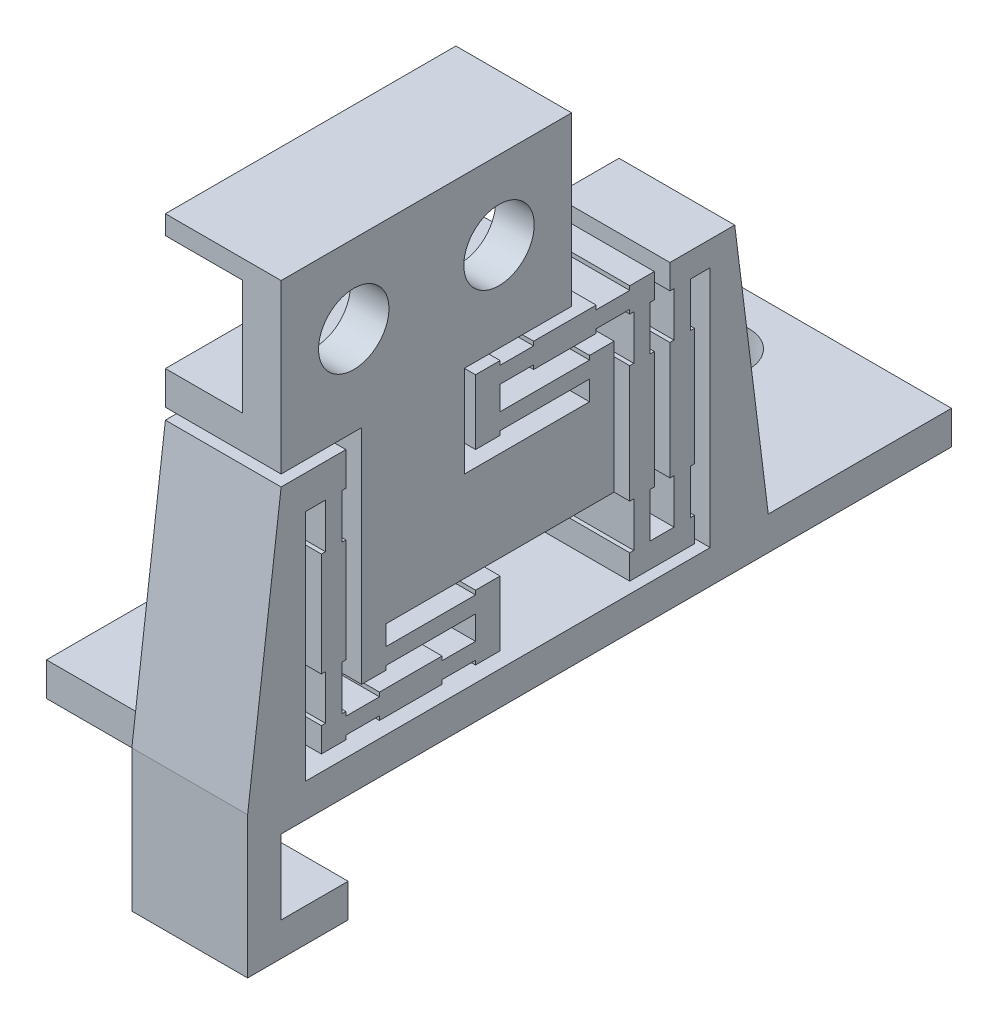
SolidWorks part; units mm, degrees
ref_plane "Front Plane" through (0, 0, 0) normal (0, 0, 1) x (1, 0, 0)
ref_plane "Top Plane" through (0, 0, 0) normal (0, 1, 0) x (1, 0, 0)
ref_plane "Right Plane" through (0, 0, 0) normal (1, 0, 0) x (0, 0, -1)
sketch "Sketch1" plane through (0, 0, 0) normal (1, 0, 0) x (0, 0, -1)
  line L0 (0, 0) -> (13, 0)
  line L1 (13, 0) -> (13, -7.5)
  line L2 (0, 0) -> (0, -7.5)
  line L3 (0, -7.5) -> (3.6, -7.5)
  line L4 (3.6, -7.5) -> (3.6, -17.45)
  line L5 (4.7, -17.2667) -> (8.7, -17.2667)
  line L6 (8.7, -17.2667) -> (8.7, -18.3333)
  line L7 (2.9, -18.15) -> (2.7167, -18.15)
  line L8 (2.9, -16.15) -> (2.9, -11.5)
  line L9 (2.9, -8) -> (0, -8)
  line L10 (0, -8) -> (-1.5, -19.95)
  line L11 (13, -7.5) -> (8.2, -7.5)
  line L12 (8.2, -7.5) -> (8.2, -11.6)
  line L13 (8.2, -11.6) -> (13.8, -11.6)
  line L14 (13.8, -11.6) -> (13.8, -10.7167)
  line L15 (9.8, -10.9) -> (8.7, -10.9)
  line L16 (8.7, -10.9) -> (8.7, -8)
  line L17 (8.7, -8) -> (9.8, -8)
  line L18 (14.9, -9.8) -> (14.9, -15.65)
  line L19 (14.9, -15.65) -> (4.7, -15.65)
  line L20 (4.7, -15.65) -> (4.7, -16.5333)
  line L21 (8.7, -16.35) -> (9.8, -16.35)
  line L22 (9.8, -16.35) -> (9.8, -19.25)
  line L23 (9.8, -19.25) -> (8.7, -19.25)
  line L24 (1.8, -19.25) -> (1.8, -18.15)
  line L25 (1.9833, -9.5) -> (1.1, -9.5)
  line L26 (1.1, -9.5) -> (1.1, -19.95)
  line L27 (1.1, -19.95) -> (19.2, -19.95)
  line L28 (14.9, -9.8) -> (13.8, -9.8)
  line L29 (9.8, -9.9833) -> (9.8, -8.9167)
  line L30 (11.3, -9.1) -> (14.1, -9.1)
  line L31 (15.6, -11.1) -> (15.6, -16.35)
  line L32 (16.7, -8) -> (16.7, -9.1)
  line L33 (16.5167, -18.35) -> (17.5833, -18.35)
  line L34 (17.4, -16.35) -> (17.4, -11.1)
  line L35 (17.4, -8) -> (20.3, -8)
  line L36 (15.6, -19.45) -> (18.5, -19.45)
  line L37 (18.5, -19.45) -> (18.5, -18.35)
  line L38 (18.3167, -9.1) -> (19.2, -9.1)
  line L39 (19.2, -9.1) -> (19.2, -19.95)
  line L45 (0, -21.45) -> (21.8, -21.45)
  line L47 (21.8, -21.45) -> (21.8, -19.95)
  line L49 (20.3, -8) -> (21.8, -19.95)
  line L51 (-1.5, -19.95) -> (-1.5, -26.28)
  line L52 (-1.5, -26.28) -> (3, -26.28)
  line L53 (3, -26.28) -> (3, -24.78)
  line L54 (3, -24.78) -> (0, -24.78)
  line L55 (0, -24.78) -> (0, -21.45)
  line L57 (1.9833, -9.5) -> (1.9833, -11.5)
  line L58 (1.9833, -11.5) -> (1.8, -11.5)
  line L59 (2.9, -9.5) -> (2.7167, -9.5)
  line L60 (2.7167, -9.5) -> (2.7167, -11.5)
  line L61 (2.7167, -11.5) -> (2.9, -11.5)
  line L63 (2.7167, -18.15) -> (2.7167, -16.15)
  line L64 (2.7167, -16.15) -> (2.9, -16.15)
  line L65 (1.8, -18.15) -> (1.9833, -18.15)
  line L66 (1.9833, -18.15) -> (1.9833, -16.15)
  line L67 (1.9833, -16.15) -> (1.8, -16.15)
  line L75 (15.6, -9.1) -> (15.7833, -9.1)
  line L76 (15.7833, -9.1) -> (15.7833, -11.1)
  line L77 (15.7833, -11.1) -> (15.6, -11.1)
  line L78 (16.7, -9.1) -> (16.5167, -9.1)
  line L79 (16.5167, -9.1) -> (16.5167, -11.1)
  line L80 (2.9, -9.5) -> (2.9, -8)
  line L81 (1.8, -16.15) -> (1.8, -11.5)
  line L82 (16.5167, -11.1) -> (16.7, -11.1)
  line L83 (16.7, -11.1) -> (16.7, -16.35)
  line L84 (16.7, -16.35) -> (16.5167, -16.35)
  line L85 (16.5167, -16.35) -> (16.5167, -18.35)
  line L86 (15.6, -16.35) -> (15.7833, -16.35)
  line L87 (15.7833, -16.35) -> (15.7833, -18.35)
  line L88 (15.7833, -18.35) -> (15.6, -18.35)
  line L89 (15.6, -18.35) -> (15.6, -19.45)
  line L90 (17.4, -16.35) -> (17.5833, -16.35)
  line L91 (17.5833, -16.35) -> (17.5833, -18.35)
  line L92 (18.5, -16.35) -> (18.3167, -16.35)
  line L93 (18.3167, -16.35) -> (18.3167, -18.35)
  line L94 (18.3167, -18.35) -> (18.5, -18.35)
  line L95 (18.5, -11.1) -> (18.3167, -11.1)
  line L96 (18.3167, -11.1) -> (18.3167, -9.1)
  line L97 (17.4, -11.1) -> (17.5833, -11.1)
  line L98 (17.5833, -11.1) -> (17.5833, -9.1)
  line L99 (17.5833, -9.1) -> (17.4, -9.1)
  line L100 (17.4, -9.1) -> (17.4, -8)
  line L101 (18.5, -16.35) -> (18.5, -11.1)
  line L102 (9.8, -8) -> (9.8, -8.1833)
  line L103 (9.8, -8.1833) -> (11.3, -8.1833)
  line L104 (11.3, -8.1833) -> (11.3, -8)
  line L105 (11.3, -9.1) -> (11.3, -8.9167)
  line L106 (11.3, -8.9167) -> (9.8, -8.9167)
  line L108 (15.6, -8) -> (15.6, -8.1833)
  line L109 (15.6, -8.1833) -> (14.1, -8.1833)
  line L110 (14.1, -8.1833) -> (14.1, -8)
  line L111 (14.1, -9.1) -> (14.1, -8.9167)
  line L112 (14.1, -8.9167) -> (15.6, -8.9167)
  line L113 (15.6, -8.9167) -> (15.6, -9.1)
  line L114 (11.3, -8) -> (14.1, -8)
  line L115 (15.6, -8) -> (16.7, -8)
  line L116 (2.9, -18.15) -> (2.9, -18.3333)
  line L117 (2.9, -18.3333) -> (4.4, -18.3333)
  line L118 (2.9, -19.25) -> (2.9, -19.0667)
  line L119 (2.9, -19.0667) -> (4.4, -19.0667)
  line L120 (8.7, -19.0667) -> (8.7, -19.25)
  line L121 (4.7, -17.2667) -> (4.7, -17.45)
  line L122 (4.7, -17.45) -> (3.6, -17.45)
  line L123 (8.7, -16.35) -> (8.7, -16.5333)
  line L124 (8.7, -16.5333) -> (4.7, -16.5333)
  line L125 (4.4, -18.3333) -> (4.4, -18.15)
  line L126 (4.4, -18.15) -> (7.2, -18.15)
  line L127 (7.2, -18.15) -> (7.2, -18.3333)
  line L128 (7.2, -19.25) -> (4.4, -19.25)
  line L129 (4.4, -19.25) -> (4.4, -19.0667)
  line L130 (7.2, -19.0667) -> (7.2, -19.25)
  line L131 (7.2, -18.3333) -> (8.7, -18.3333)
  line L132 (7.2, -19.0667) -> (8.7, -19.0667)
  line L133 (9.8, -10.9) -> (9.8, -10.7167)
  line L134 (9.8, -10.7167) -> (13.8, -10.7167)
  line L135 (13.8, -9.8) -> (13.8, -9.9833)
  line L136 (13.8, -9.9833) -> (9.8, -9.9833)
  line L137 (2.9, -19.25) -> (1.8, -19.25)
  point P40 (18.3167, -10.1)
  point P135 (11.8, -9.9833)
  point P136 (9.25, -10.9)
  dimension "D2" = 2.9
  dimension "D3" = 1.1
  dimension "D6" = 1.1
  dimension "D8" = 2.9
  dimension "D9" = 1.1
  dimension "D11" = 2.9
  dimension "D12" = 7.5
  dimension "D13" = 0.5
  dimension "D14" = 1.5
  dimension "D15" = 11.25
  dimension "D16" = 0.7
  dimension "D17" = 1.5
  dimension "D20" = 13
  dimension "D21" = 0.7
  dimension "D22" = 2.9
  dimension "D25" = 0.7
  dimension "D26" = 1.1
  dimension "D27" = 0.5
  dimension "D29" = 1.1
  dimension "D28" = 1.1
  dimension "D30" = 1.1
  dimension "D18" = 1.5
  dimension "D19" = 4.5
  dimension "D32" = 1.5
  dimension "D33" = 3.33
  dimension "D34" = 2
  dimension "D35" = 0.7333
  dimension "D4" = 0.7
  dimension "D23" = 0.7333
  dimension "D41" = 2
  dimension "D10" = 0.7
  dimension "D42" = 2
  dimension "D43" = 0.7333
  dimension "D31" = 0.7
  dimension "D44" = 0.7333
  dimension "D45" = 2
  dimension "D46" = 0.7333
  dimension "D47" = 2
  dimension "D36" = 2
  dimension "D38" = 1.5
  dimension "D39" = 0.7333
  dimension "D40" = 0.7333
  dimension "D7" = 1.1
  dimension "D24" = 0.7333
  dimension "D5" = 1.5
  dimension "D48" = 8
  dimension "D49" = 0.7333
  dimension "D50" = 0.7
  dimension "D51" = 1.1
  dimension "D37" = 1.1
  dimension "D52" = 0.7333
  dimension "D53" = 0.7
  dimension "D54" = 1.1
  dimension "D55" = 0.7
  dimension "D56" = 1.1
  dimension "D57" = 8
  dimension "D58" = 0.5
extrude "Boss-Extrude1" add sketch "Sketch1" along normal blind 5.18
sketch "Sketch2" plane through (0, 0, 0) normal (0, 0, 1) x (1, 0, 0)
  line L0 (5.18, 0) -> (5.18, -7.5) construction
  line L1 (5.18, -0.85) -> (1.73, -0.85)
  line L2 (5.18, -0.85) -> (5.18, -6)
  line L3 (5.18, -6) -> (1.73, -6)
  line L4 (1.73, -0.85) -> (1.73, -6)
  line L6 (5.18, -7.5) -> (0, -7.5) construction
  line L7 (5.18, 0) -> (0, 0) construction
  dimension "D1" = 3.45
  dimension "D2" = 1.5
  dimension "D3" = 0.85
extrude "Cut-Extrude1" cut sketch "Sketch2" against normal up to next
sketch "Sketch3" plane through (0, -21.45, 0) normal (0, -1, 0) x (1, 0, 0)
  line L0 (0, 1.5) -> (0, -3) construction
  line L1 (0, -30) -> (10.5, -30)
  line L2 (0, -30) -> (0, 0)
  line L3 (0, 0) -> (10.5, 0)
  line L4 (10.5, -30) -> (10.5, 0)
  line L6 (5.18, 0) -> (5.18, -21.8) construction
  line L7 (5.18, 1.5) -> (0, 1.5) construction
  circle A0 centre (7.62, -14.98) radius 1.575
  circle A1 centre (7.62, -26.98) radius 1.575
  dimension "D3" = 3.15
  dimension "D1" = 10.5
  dimension "D2" = 16.48
  dimension "D4" = 12
  dimension "D5" = 30
  dimension "D6" = 2.44
extrude "Boss-Extrude2" add sketch "Sketch3" against normal blind 1.5
sketch "Sketch7" plane through (0, 0, 0) normal (-1, 0, 0) x (0, 0, 1)
  line L0 (-13, 0) -> (0, 0) construction
  line L1 (0, 0) -> (0, -7.5) construction
  circle A0 centre (-3.25, -3.5) radius 1.575
  circle A1 centre (-9.75, -3.5) radius 1.575
  dimension "D1" = 3.15
  dimension "D2" = 3.5
  dimension "D3" = 3.25
  dimension "D4" = 6.5
extrude "Cut-Extrude3" cut sketch "Sketch7" against normal up to next
mirror "Mirror3" about plane through (0, 0, 0) normal (1, 0, 0) of bodies 105
delete or keep bodies "Body-Delete/Keep 1" type delete bodies bodies 105
equation "\"FlexureWidth\"= 1.1"
equation "\"FlexureGap\"= 0.7"
equation "\"DoubleFlexureWidth\"= 2 * \"FlexureWidth\" + \"FlexureGap\""
equation "\"D2@Sketch1\"=\"DoubleFlexureWidth\""
equation "\"D3@Sketch1\"=\"FlexureWidth\""
equation "\"HorizontalFlexureLength\"= 5mm"
equation "\"FlexureJointWidth\"=1.5"
equation "\"D6@Sketch1\"=\"FlexureWidth\""
equation "\"D8@Sketch1\"=\"DoubleFlexureWidth\""
equation "\"D9@Sketch1\"=\"FlexureWidth\""
equation "\"D11@Sketch1\"=\"DoubleFlexureWidth\""
equation "\"HeadHeight\"= 7.5"
equation "\"VerticalFlexureLength\"= 11.25"
equation "\"MinGap\"=0.5"
equation "\"D12@Sketch1\"=\"HeadHeight\""
equation "\"D13@Sketch1\"=\"MinGap\""
equation "\"D14@Sketch1\"=\"FlexureJointWidth\""
equation "\"D15@Sketch1\"=\"VerticalFlexureLength\""
equation "\"D16@Sketch1\"=\"FlexureGap\""
equation "\"D17@Sketch1\"=\"FlexureJointWidth\""
equation "\"BaseplateHeight+Tolerance\"= 3.33"
equation "\"HeadWidth\"= 13"
equation "\"D20@Sketch1\"=\"HeadWidth\""
equation "\"D21@Sketch1\"=\"FlexureGap\""
equation "\"D22@Sketch1\"=\"DoubleFlexureWidth\""
equation "\"D25@Sketch1\"=\"FlexureGap\""
equation "\"D26@Sketch1\"=\"FlexureWidth\""
equation "\"D27@Sketch1\"=\"MinGap\""
equation "\"D29@Sketch1\"=\"FlexureWidth\""
equation "\"D30@Sketch1\"=\"FlexureWidth\""
equation "\"D1@Boss-Extrude1\"=5.18"
equation "\"D32@Sketch1\"=\"FlexureJointWidth\""
equation "\"D18@Sketch1\"=\"FlexureJointWidth\""
equation "\"NeckLength\"=2"
equation "\"NeckWidth\"= \"FlexureWidth\" * 2 / 3"
equation "\"D35@Sketch1\"=\"NeckWidth\""
equation "\"D4@Sketch1\"=\"FlexureGap\""
equation "\"D34@Sketch1\"=\"NeckLength\""
equation "\"D23@Sketch1\"=\"NeckWidth\""
equation "\"D41@Sketch1\"=\"NeckLength\""
equation "\"D10@Sketch1\"=\"FlexureGap\""
equation "\"D42@Sketch1\"=\"NeckLength\""
equation "\"D43@Sketch1\"=\"NeckWidth\""
equation "\"D31@Sketch1\"=\"FlexureGap\""
equation "\"D44@Sketch1\"=\"NeckWidth\""
equation "\"D45@Sketch1\"=\"NeckLength\""
equation "\"D46@Sketch1\"=\"NeckWidth\""
equation "\"D47@Sketch1\"=\"NeckLength\""
equation "\"D36@Sketch1\"=\"NeckLength\""
equation "\"D38@Sketch1\"=\"NeckLength2\""
equation "\"D39@Sketch1\"=\"NeckWidth\""
equation "\"D40@Sketch1\"=\"NeckWidth\""
equation "\"D7@Sketch1\"=\"FlexureWidth\""
equation "\"D24@Sketch1\"=\"NeckWidth\""
equation "\"NeckLength2\"= 1.5"
equation "\"D5@Sketch1\"=\"NeckLength2\""
equation "\"D49@Sketch1\"=\"NeckWidth\""
equation "\"D50@Sketch1\"=\"FlexureGap\""
equation "\"D51@Sketch1\"=\"FlexureWidth\""
equation "\"D37@Sketch1\"=\"FlexureWidth\""
equation "\"D52@Sketch1\"=\"NeckWidth\""
equation "\"D53@Sketch1\"=\"FlexureGap\""
equation "\"D54@Sketch1\"=\"FlexureWidth\""
equation "\"D55@Sketch1\"=\"FlexureGap\""
equation "\"D56@Sketch1\"=\"FlexureWidth\""
equation "\"D28@Sketch1\"=\"FlexureWidth\""
equation "\"D58@Sketch1\"=\"MinGap\""
